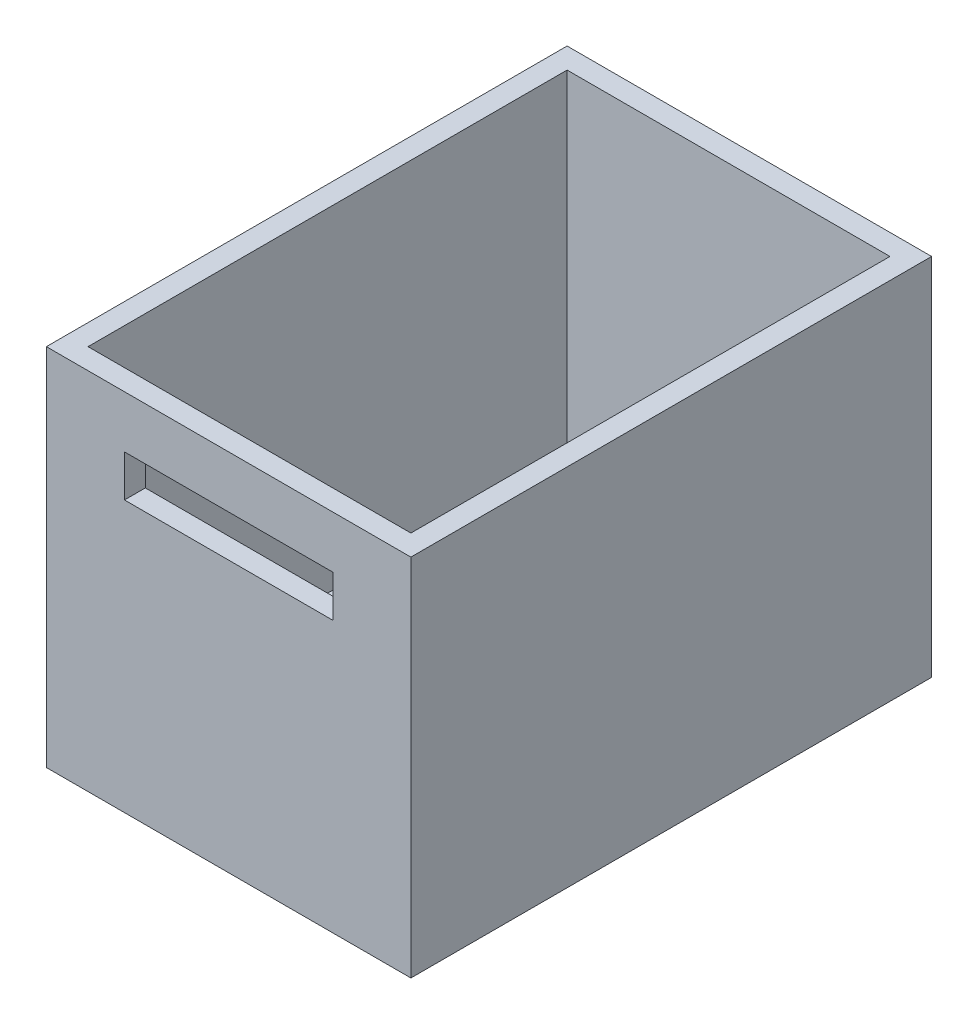
SolidWorks part; units mm, degrees
ref_plane "Front Plane" through (0, 0, 0) normal (0, 0, 1) x (1, 0, 0)
ref_plane "Top Plane" through (0, 0, 0) normal (0, 1, 0) x (1, 0, 0)
ref_plane "Right Plane" through (0, 0, 0) normal (1, 0, 0) x (0, 0, -1)
sketch "Sketch1" plane through (0, 0, 0) normal (0, 1, 0) x (1, 0, 0)
  line L1 (-87.5, 125) -> (87.5, 125)
  line L2 (-87.5, 125) -> (-87.5, -125)
  line L3 (-87.5, -125) -> (87.5, -125)
  line L4 (87.5, 125) -> (87.5, -125)
  line L5 (-87.5, 125) -> (87.5, -125) construction
  line L6 (-87.5, -125) -> (87.5, 125) construction
  point P0 (0, 0)
  dimension "D1" = 250
  dimension "D2" = 175
extrude "Boss-Extrude1" add sketch "Sketch1" along normal blind 175
sketch "Sketch2" plane through (0, 175, 0) normal (0, 1, 0) x (1, 0, 0)
  line L1 (-77.5, 115) -> (77.5, 115)
  line L2 (-77.5, 115) -> (-77.5, -115)
  line L3 (-77.5, -115) -> (77.5, -115)
  line L4 (77.5, 115) -> (77.5, -115)
  line L5 (-77.5, 115) -> (77.5, -115) construction
  line L6 (-77.5, -115) -> (77.5, 115) construction
  point P0 (0, 0)
  dimension "D1" = 155
  dimension "D2" = 230
extrude "Cut-Extrude1" cut sketch "Sketch2" against normal blind 160
sketch "Sketch3" plane through (0, 0, 125) normal (0, 0, 1) x (1, 0, 0)
  line L1 (-50, 150) -> (50, 150)
  line L2 (-50, 150) -> (-50, 130)
  line L3 (-50, 130) -> (50, 130)
  line L4 (50, 150) -> (50, 130)
  line L5 (-50, 150) -> (50, 130) construction
  line L6 (-50, 130) -> (50, 150) construction
  point P0 (0, 140)
  dimension "D1" = 130
  dimension "D2" = 100
  dimension "D3" = 20
extrude "Cut-Extrude2" cut sketch "Sketch3" against normal blind 100
